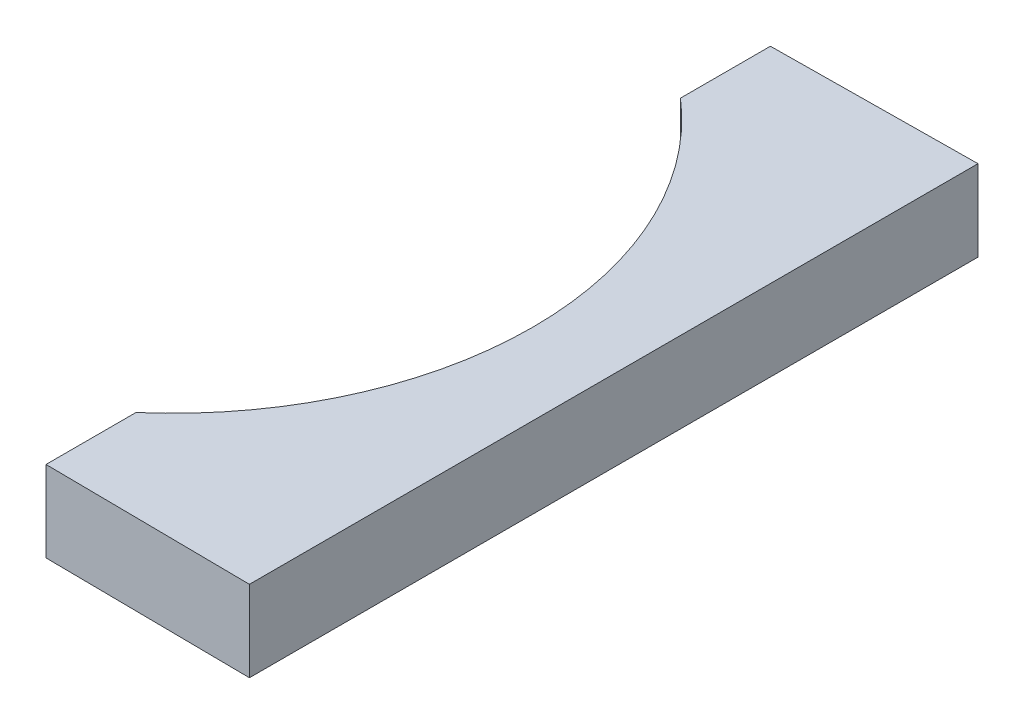
SolidWorks part; units mm, degrees
ref_plane "Front Plane" through (0, 0, 0) normal (0, 0, 1) x (1, 0, 0)
ref_plane "Top Plane" through (0, 0, 0) normal (0, 1, 0) x (1, 0, 0)
ref_plane "Right Plane" through (0, 0, 0) normal (1, 0, 0) x (0, 0, -1)
sketch "Sketch1" plane through (0, 0, 0) normal (0, 1, 0) x (1, 0, 0)
  line L0 (0, -4) -> (0, 4) construction
  line L4 (0, 4) -> (4.9, 4.05)
  line L5 (4.9, 4.05) -> (4.9, -4.05)
  line L6 (4.9, -4.05) -> (0, -4)
  line L7 (4, 0) -> (4.9, 0) construction
  line L8 (2.6152, -4.0267) -> (2.6152, -3.0267)
  line L9 (2.6152, 4.0267) -> (2.6152, 3.0267)
  circle A0 centre (0, 0) radius 4 construction
  arc A1 (0, 4) -> (0, -4) centre (0, 0) cw
  point P6 (4, 0)
  point P14 (-9.1107, -0.628)
  point P15 (0, 0)
  dimension "D1" = 8
  dimension "D2" = 0.9
  dimension "D3" = 8.1
  dimension "D4" = 1
extrude "Boss-Extrude1" add sketch "Sketch1" along normal blind 0.9 contours L9 A1 L8 L6 L5 L4
